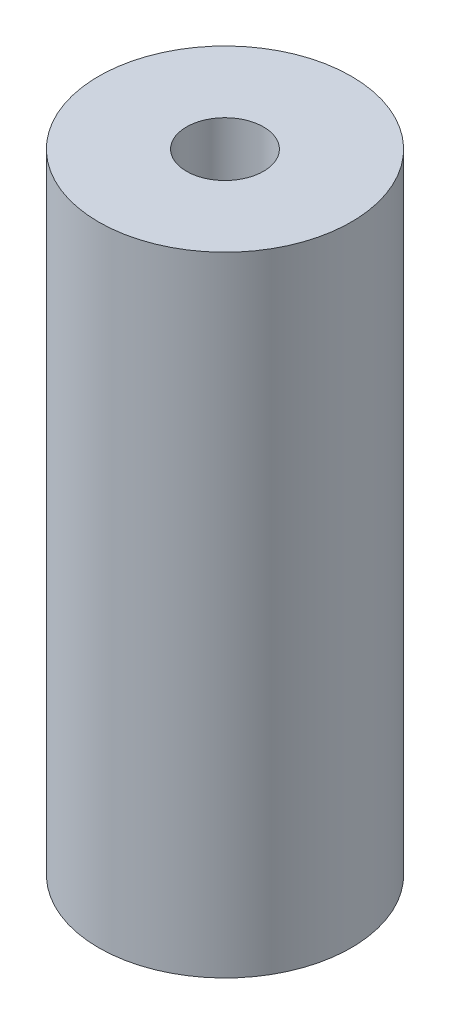
SolidWorks part; units mm, degrees
material "PTFE (general)"
ref_plane "Ön Düzlem" through (0, 0, 0) normal (0, 0, 1) x (1, 0, 0)
ref_plane "Üst Düzlem" through (0, 0, 0) normal (0, 1, 0) x (1, 0, 0)
ref_plane "Sağ Düzlem" through (0, 0, 0) normal (1, 0, 0) x (0, 0, -1)
sketch "Sketch1" plane through (0, 0, 0) normal (0, 1, 0) x (1, 0, 0)
  circle A0 centre (0, 0) radius 0.625
  circle A1 centre (0, 0) radius 2.05
  dimension "D1" = 4.1
  dimension "D2" = 1.25
extrude "Boss-Extrude1" add sketch "Sketch1" along normal blind 10.2
